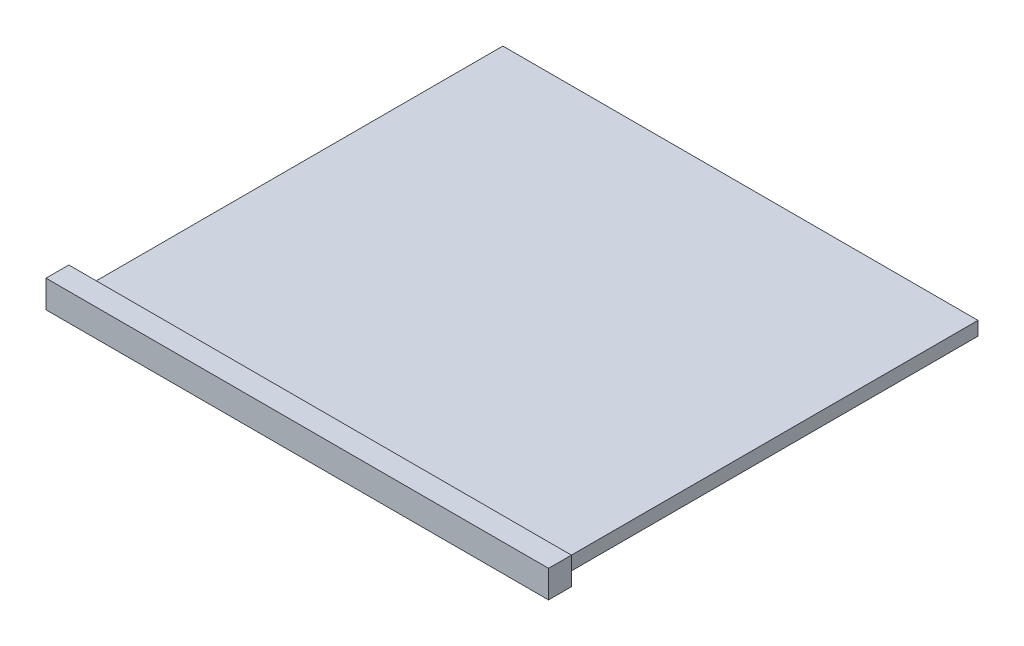
SolidWorks part; units mm, degrees
ref_plane "Front Plane" through (0, 0, 0) normal (0, 0, 1) x (1, 0, 0)
ref_plane "Top Plane" through (0, 0, 0) normal (0, 1, 0) x (1, 0, 0)
ref_plane "Right Plane" through (0, 0, 0) normal (1, 0, 0) x (0, 0, -1)
sketch "Sketch1" plane through (0, 0, 0) normal (0, 0, 1) x (1, 0, 0)
  line L5 (-52, -3) -> (52, -3)
  line L6 (-52, -3) -> (-52, 3)
  line L7 (-52, 3) -> (52, 3)
  line L8 (52, -3) -> (52, 3)
  line L9 (-52, -3) -> (52, 3) construction
  line L10 (-52, 3) -> (52, -3) construction
  point P0 (0, 0)
  dimension "D1" = 104
  dimension "D2" = 6
extrude "Boss-Extrude1" add sketch "Sketch1" against normal blind 5
ref_plane "Plane1" through (0, 0, -5) normal (0, 0, -1) x (-1, 0, 0)
sketch "Sketch2" plane through (0, 0, -5) normal (0, 0, -1) x (-1, 0, 0)
  line L0 (52, 3) -> (52, -3) construction
  line L1 (-52, -3) -> (52, -3)
  line L2 (-52, -3) -> (-52, 0)
  line L3 (-52, 0) -> (52, 0)
  line L4 (52, -3) -> (52, 0)
extrude "Boss-Extrude2" add sketch "Sketch2" along normal blind 92
sketch "Sketch3" plane through (52, 0, 0) normal (1, 0, 0) x (0, 0, -1)
  line L1 (5, 3) -> (0, 3)
  line L2 (5, 3) -> (5, -3)
  line L3 (5, -3) -> (0, -3)
  line L4 (0, 3) -> (0, -3)
extrude "Boss-Extrude3" add sketch "Sketch3" along normal blind 3
sketch "Sketch4" plane through (-52, 0, 0) normal (-1, 0, 0) x (0, 0, 1)
  line L0 (-97, -3) -> (0, -3) construction
  line L1 (0, 3) -> (-5, 3)
  line L2 (0, 3) -> (0, -3)
  line L3 (0, -3) -> (-5, -3)
  line L4 (-5, 3) -> (-5, -3)
extrude "Boss-Extrude4" add sketch "Sketch4" along normal blind 3
